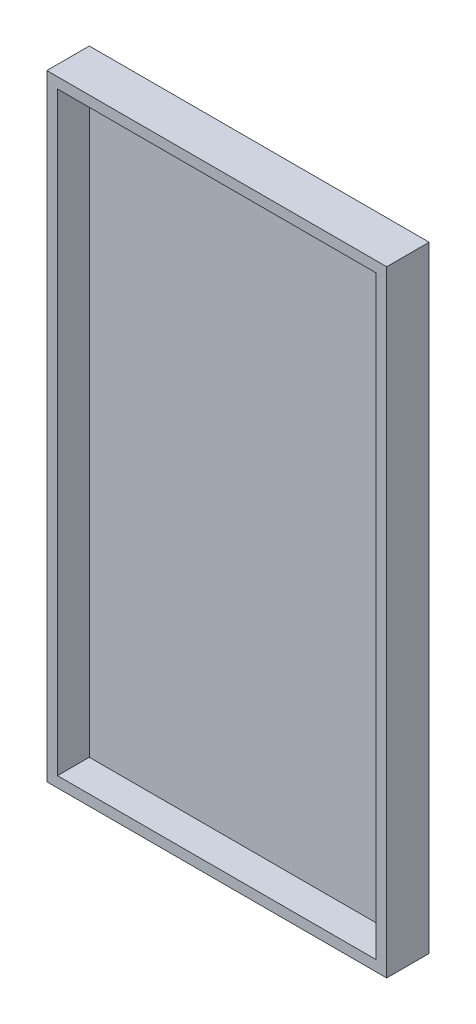
SolidWorks part; units mm, degrees
ref_plane "Front Plane" through (0, 0, 0) normal (0, 0, 1) x (1, 0, 0)
ref_plane "Top Plane" through (0, 0, 0) normal (0, 1, 0) x (1, 0, 0)
ref_plane "Right Plane" through (0, 0, 0) normal (1, 0, 0) x (0, 0, -1)
sketch "Sketch1" plane through (0, 0, 0) normal (0, 0, 1) x (1, 0, 0)
  line L1 (-16, -29) -> (16, -29)
  line L2 (-16, -29) -> (-16, 29)
  line L3 (-16, 29) -> (16, 29)
  line L4 (16, -29) -> (16, 29)
  line L5 (-16, -29) -> (16, 29) construction
  line L6 (-16, 29) -> (16, -29) construction
  point P0 (0, 0)
  dimension "D1" = 32
  dimension "D2" = 58
extrude "Boss-Extrude1" add sketch "Sketch1" along normal mid plane 4
shell "Shell1" thickness 1
sketch "Sketch2" plane through (0, -29, 0) normal (0, -1, 0) x (1, 0, 0)
  line L0 (-16, 2) -> (-15, 2)
  line L2 (-16, 2) -> (16, 2) construction
  arc A0 (-16, 2) -> (-14, 9) centre (-11.5, 4.5) cw
  ellipse E0 centre (-14, 2) end of major axis (-14, 9) minor radius 1 (-14, 9) -> (-15, 2) ccw
  dimension "D1" = 1
